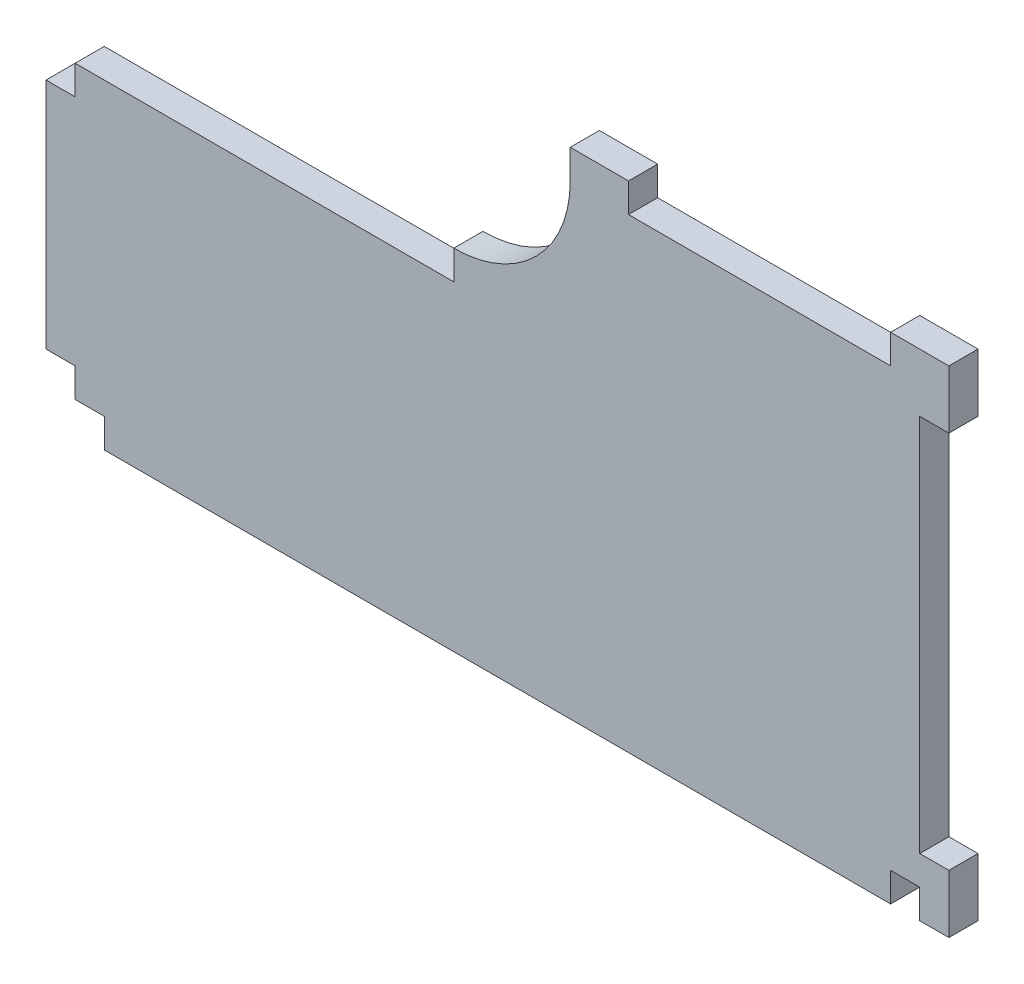
SolidWorks part; units mm, degrees
ref_plane "Front Plane" through (0, 0, 0) normal (0, 0, 1) x (1, 0, 0)
ref_plane "Top Plane" through (0, 0, 0) normal (0, 1, 0) x (1, 0, 0)
ref_plane "Right Plane" through (0, 0, 0) normal (1, 0, 0) x (0, 0, -1)
sketch "Sketch1" plane through (0, 0, 0) normal (0, 0, 1) x (1, 0, 0)
  line L1 (-114.3, -6.35) -> (82.55, -6.35)
  line L2 (-114.3, -6.35) -> (-114.3, 101.6)
  line L3 (-114.3, 101.6) -> (82.55, 101.6)
  line L4 (82.55, -6.35) -> (82.55, 101.6)
  dimension "D1" = 196.85
  dimension "D2" = 107.95
extrude "Boss-Extrude1" add sketch "Sketch1" against normal blind 6.35
sketch "Sketch2" plane through (0, 0, 0) normal (0, 0, 1) x (1, 0, 0)
  line L0 (0, 101.6) -> (0, 95.25)
  line L1 (82.55, 101.6) -> (-114.3, 101.6) construction
  line L2 (0, 146.05) -> (0, 101.6) construction
  line L3 (-114.3, 101.6) -> (-114.3, 69.85)
  line L4 (69.85, 101.6) -> (12.7, 101.6)
  line L5 (12.7, 101.6) -> (12.7, 95.25)
  line L6 (12.7, 95.25) -> (69.85, 95.25)
  line L7 (69.85, 95.25) -> (69.85, 101.6)
  line L8 (69.85, 101.6) -> (12.7, 101.6)
  line L9 (12.7, 101.6) -> (12.7, 95.25)
  line L10 (12.7, 95.25) -> (69.85, 95.25)
  line L11 (69.85, 95.25) -> (69.85, 101.6)
  line L12 (76.2, 88.9) -> (76.2, 6.35)
  line L13 (76.2, 6.35) -> (82.55, 6.35)
  line L14 (82.55, 6.35) -> (82.55, 88.9)
  line L15 (82.55, 88.9) -> (76.2, 88.9)
  line L16 (76.2, 88.9) -> (76.2, 6.35)
  line L17 (76.2, 6.35) -> (82.55, 6.35)
  line L18 (82.55, 6.35) -> (82.55, 88.9)
  line L19 (82.55, 88.9) -> (76.2, 88.9)
  line L20 (-114.3, 101.6) -> (-114.3, -6.35) construction
  line L21 (-107.95, 69.85) -> (-25.4, 69.85) construction
  line L22 (-114.3, -6.35) -> (-101.6, -6.35)
  line L23 (-114.3, 101.6) -> (0, 101.6)
  line L24 (-25.4, 69.85) -> (-25.4, 63.5)
  line L25 (-25.4, 63.5) -> (-107.95, 63.5)
  line L26 (-107.95, 63.5) -> (-107.95, 57.15)
  line L27 (-107.95, 69.85) -> (-114.3, 69.85) construction
  line L28 (76.2, 0) -> (76.2, -6.35)
  line L29 (82.55, -6.35) -> (82.55, 101.6) construction
  line L32 (76.2, 0) -> (69.85, 0) construction
  line L33 (76.2, -6.35) -> (69.85, -6.35)
  line L35 (76.2, 0) -> (69.85, 0)
  line L36 (69.85, -6.35) -> (69.85, 0)
  line L37 (-107.95, -6.35) -> (-107.95, 6.35) construction
  line L40 (-107.95, 0) -> (-101.6, 0)
  line L41 (-101.6, -6.35) -> (-101.6, 0)
  line L43 (-114.3, -6.35) -> (-114.3, 6.35)
  line L44 (-114.3, 6.35) -> (-107.95, 6.35)
  line L45 (-107.95, 0) -> (-107.95, 6.35)
  line L48 (-114.3, 69.85) -> (-114.3, 57.15)
  line L49 (-114.3, 57.15) -> (-107.95, 57.15)
  arc A0 (0, 95.25) -> (-25.4, 69.85) centre (-25.4, 95.25) cw
  point P24 (0, 69.85)
  dimension "D3" = 25.4
  dimension "D4" = 6.35
  dimension "D5" = 12.7
  dimension "D6" = 12.7
  dimension "D7" = 6.35
  dimension "D8" = 6.35
  dimension "D1" = 0
  dimension "D2" = 0
extrude "Cut-Extrude1" cut sketch "Sketch2" against normal through all
